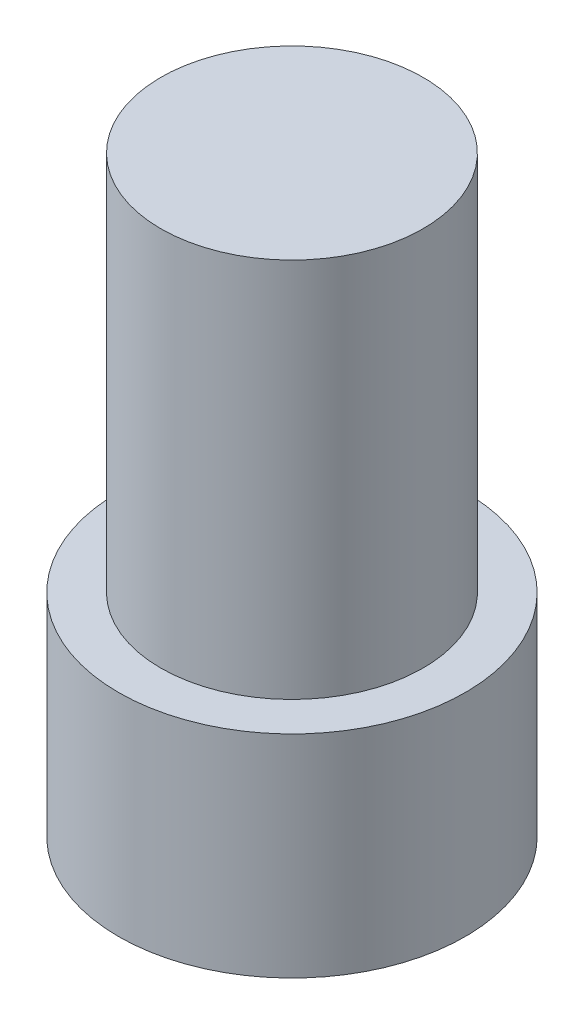
SolidWorks part; units mm, degrees
material "Brass"
ref_plane "Front Plane" through (0, 0, 0) normal (0, 0, 1) x (1, 0, 0)
ref_plane "Top Plane" through (0, 0, 0) normal (0, 1, 0) x (1, 0, 0)
ref_plane "Right Plane" through (0, 0, 0) normal (1, 0, 0) x (0, 0, -1)
sketch "Sketch4" plane through (0, 0, 0) normal (0, 1, 0) x (1, 0, 0)
  circle A0 centre (0, 0) radius 26.0417
extrude "Extrude3" add sketch "Sketch4" along normal blind 31.75
sketch "Sketch6" plane through (0, 31.75, 0) normal (0, 1, 0) x (1, 0, 0)
  circle A0 centre (0, 0) radius 19.6984
extrude "Extrude4" add sketch "Sketch6" along normal blind 57.15
